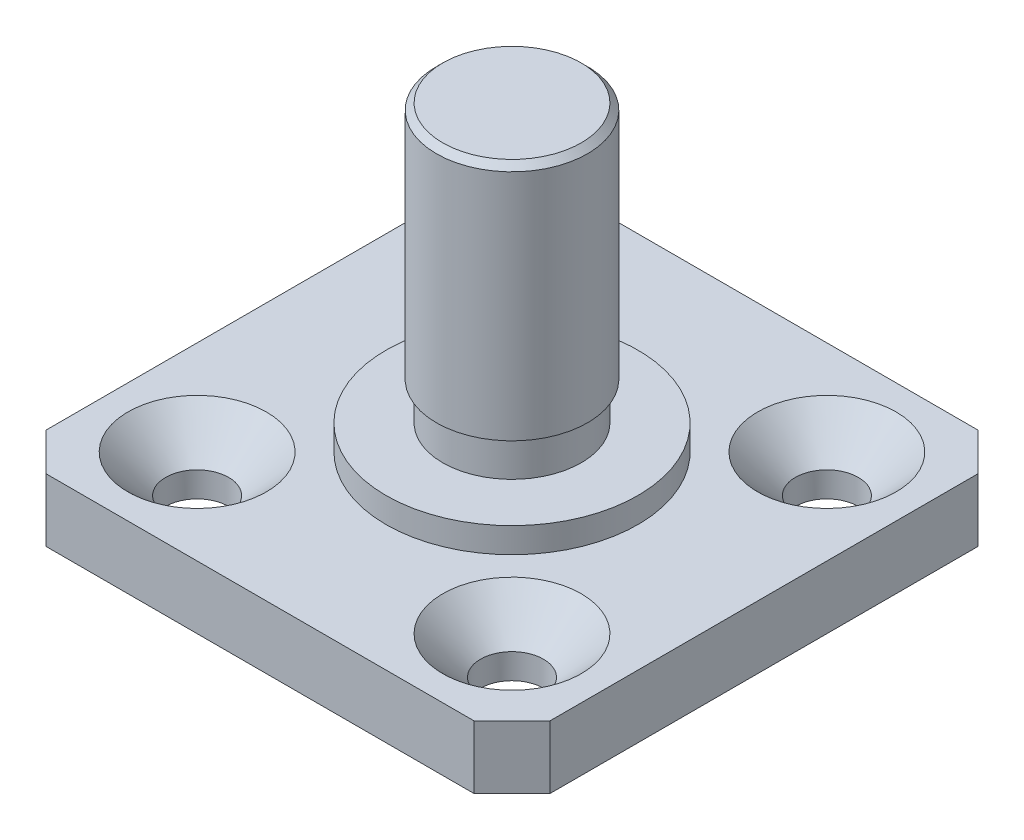
SolidWorks part; units mm, degrees
ref_plane "Спереди" through (0, 0, 0) normal (0, 0, 1) x (1, 0, 0)
ref_plane "Сверху" through (0, 0, 0) normal (0, 1, 0) x (1, 0, 0)
ref_plane "Справа" through (0, 0, 0) normal (1, 0, 0) x (0, 0, -1)
sketch "Эскиз1" plane through (0, 0, 0) normal (0, 1, 0) x (1, 0, 0)
  line L1 (-20, -20) -> (20, -20)
  line L2 (-20, -20) -> (-20, 20)
  line L3 (-20, 20) -> (20, 20)
  line L4 (20, -20) -> (20, 20)
  line L5 (0, 20) -> (0, -20) construction
  line L6 (-20, 0) -> (20, 0) construction
  point P0 (0, 0)
  dimension "D1" = 40
extrude "Бобышка-Вытянуть1" add sketch "Эскиз1" along normal blind 5
chamfer "Фаска1" distance 3 angle 45 4 edges at (-20, 2.5, -20) (20, 2.5, -20) (-20, 2.5, 20) (20, 2.5, 20)
sketch "Эскиз2" plane through (0, 5, 0) normal (0, 1, 0) x (1, 0, 0)
  circle A0 centre (0, 0) radius 10
  dimension "D1" = 20
extrude "Бобышка-Вытянуть2" add sketch "Эскиз2" along normal blind 2
sketch "Эскиз3" plane through (0, 7, 0) normal (0, 1, 0) x (1, 0, 0)
  circle A0 centre (0, 0) radius 6
  dimension "D1" = 12
extrude "Бобышка-Вытянуть3" add sketch "Эскиз3" along normal blind 22
sketch "Эскиз4" plane through (0, 7, 0) normal (0, 1, 0) x (1, 0, 0)
  circle A0 centre (0, 0) radius 6 construction
  circle A1 centre (0, 0) radius 6
  circle A4 centre (0, 0) radius 5.5
  circle A5 centre (0, 0) radius 5.5
  dimension "D1" = 0.5
extrude "Вырез-Вытянуть1" cut sketch "Эскиз4" along normal blind 3
sketch "Эскиз5" plane through (0, 5, 0) normal (0, 1, 0) x (1, 0, 0)
  line L0 (0, 0) -> (0, 8.071) construction
  line L1 (0, 0) -> (4.4681, 0) construction
  circle A0 centre (-12.5, 12.5) radius 2.5
  circle A1 centre (12.5, 12.5) radius 2.5
  circle A2 centre (12.5, -12.5) radius 2.5
  circle A3 centre (-12.5, -12.5) radius 2.5
  dimension "D1" = 5
  dimension "D2" = 25
  dimension "D3" = 25
extrude "Вырез-Вытянуть2" cut sketch "Эскиз5" against normal through all
chamfer "Фаска2" distance 3 angle 45 4 edges at (-12.5, 5, 15) (12.5, 5, 15) (12.5, 5, -10) (-12.5, 5, -10)
chamfer "Фаска3" distance 0.5 angle 45 1 edges at (0, 29, 6)
